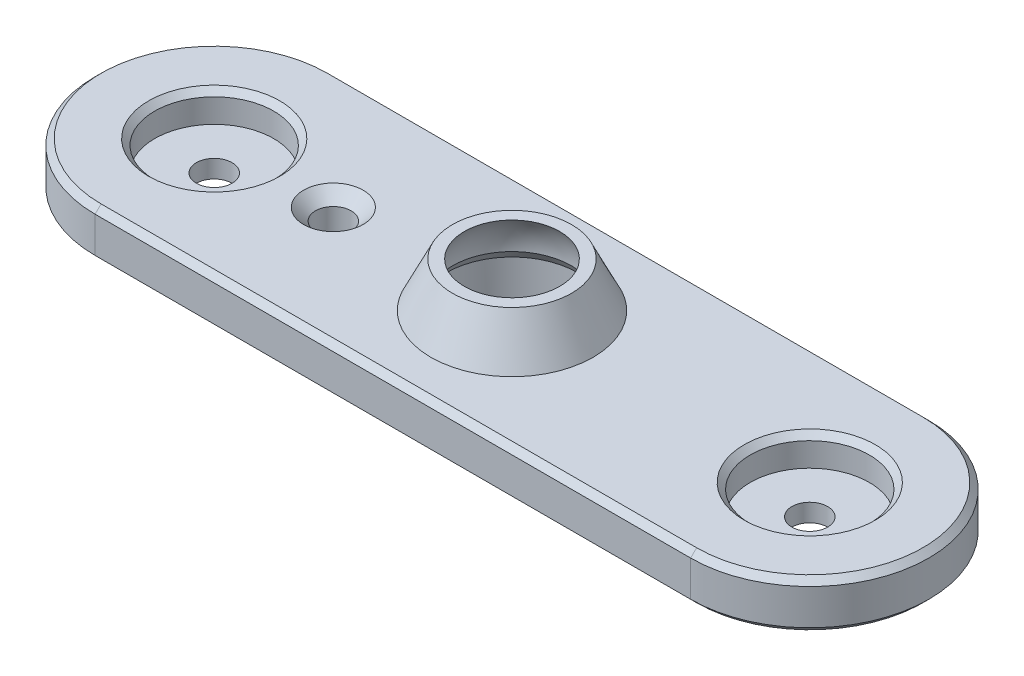
SolidWorks part; units mm, degrees
ref_plane "Alzado" through (0, 0, 0) normal (0, 0, 1) x (1, 0, 0)
ref_plane "Planta" through (0, 0, 0) normal (0, 1, 0) x (1, 0, 0)
ref_plane "Vista lateral" through (0, 0, 0) normal (1, 0, 0) x (0, 0, -1)
sketch "Croquis2" plane through (0, 0, 0) normal (0, 1, 0) x (1, 0, 0)
  line L0 (-25, 0) -> (25, 0) construction
  line L1 (-25, 10) -> (25, 10)
  line L2 (-25, -10) -> (25, -10)
  arc A0 (-25, 10) -> (-25, -10) centre (-25, 0) ccw
  arc A1 (25, -10) -> (25, 10) centre (25, 0) ccw
  circle A2 centre (-25, 0) radius 1.5
  circle A3 centre (25, 0) radius 1.5
  circle A4 centre (-15, 0) radius 1.5
  point P3 (0, 0)
  dimension "D2" = 35
  dimension "D3" = 3
  dimension "D4" = 15
  dimension "D1" = 20
extrude "Saliente-Extruir1" add sketch "Croquis2" along normal blind 4
sketch "Croquis3" plane through (0, 4, 0) normal (0, 1, 0) x (1, 0, 0)
  circle A0 centre (-25, 0) radius 5
  circle A1 centre (25, 0) radius 5
  circle A4 centre (25, 0) radius 1.5 construction
  circle A5 centre (-25, 0) radius 1.5 construction
  dimension "D1" = 10
extrude "Cortar-Extruir1" cut sketch "Croquis3" against normal blind 2.5
sketch "Croquis6" plane through (0, 4, 0) normal (0, 1, 0) x (1, 0, 0)
  circle A0 centre (0, 0) radius 5.5
  dimension "D1" = 11
extrude "Cortar-Extruir2" cut sketch "Croquis6" against normal through all
sketch "Croquis5" plane through (0, 0, 0) normal (0, 0, 1) x (1, 0, 0)
  line L0 (0, -0.25) -> (0, 9.75) construction
  line L1 (-25, 4) -> (25, 4) construction
  line L2 (0, 9.75) -> (3, 9.75) construction
  line L3 (3, 9.75) -> (3, 8.75) construction
  line L4 (0, 7.75) -> (4, 7.75) construction
  line L5 (4, 7.75) -> (6.8125, 4) construction
  line L6 (5, 4.75) -> (5.5, 4)
  line L7 (5.5, 4) -> (6.8125, 4)
  line L8 (4, 7.75) -> (5, 7.75)
  line L9 (5, 7.75) -> (6.8125, 4)
  arc A0 (3, 8.75) -> (0, -0.25) centre (0, 4.75) cw construction
  arc A1 (5, 4.75) -> (4, 7.75) centre (0, 4.75) ccw
  arc A2 (3, 8.75) -> (0, 9.75) centre (0, 4.75) ccw construction
  dimension "D1" = 5
  dimension "D5" = 1
  dimension "D3" = 0.25
  dimension "D2" = 3
  dimension "D4" = 3
revolve "Revolución1" add sketch "Croquis5" angle 360 about L0
chamfer "Chaflán1" distance 1 angle 45 2 edges at (-15, 0, 1.5) (-15, 4, 1.5)
chamfer "Chaflán2" distance 0.5 angle 45 10 edges at (0, 4, -10) (-35, 4, 0) (35, 4, 0) (0, 4, 10) (0, 0, -10) (-35, 0, 0) (35, 0, 0) (0, 0, 10) (-25, 4, 5) (25, 4, 5)
